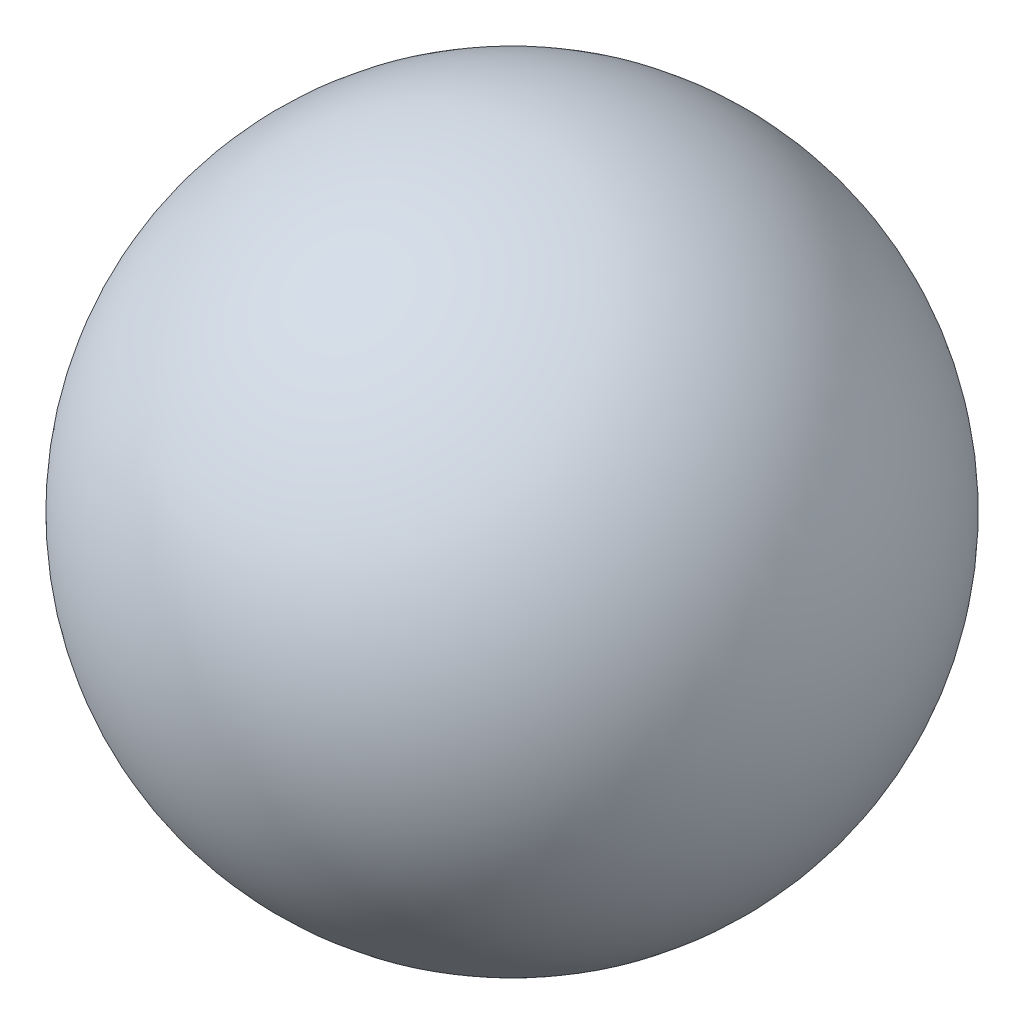
SolidWorks part; units mm, degrees
ref_plane "Front Plane" through (0, 0, 0) normal (0, 0, 1) x (1, 0, 0)
ref_plane "Top Plane" through (0, 0, 0) normal (0, 1, 0) x (1, 0, 0)
ref_plane "Right Plane" through (0, 0, 0) normal (1, 0, 0) x (0, 0, -1)
sketch "Sketch1" plane through (0, 0, 0) normal (0, 0, 1) x (1, 0, 0)
  line L0 (0, 12) -> (0, -12)
  arc A0 (0, -12) -> (0, 12) centre (0, 0) ccw
  dimension "D1" = 24
revolve "Revolve1" add sketch "Sketch1" angle 360 about L0
